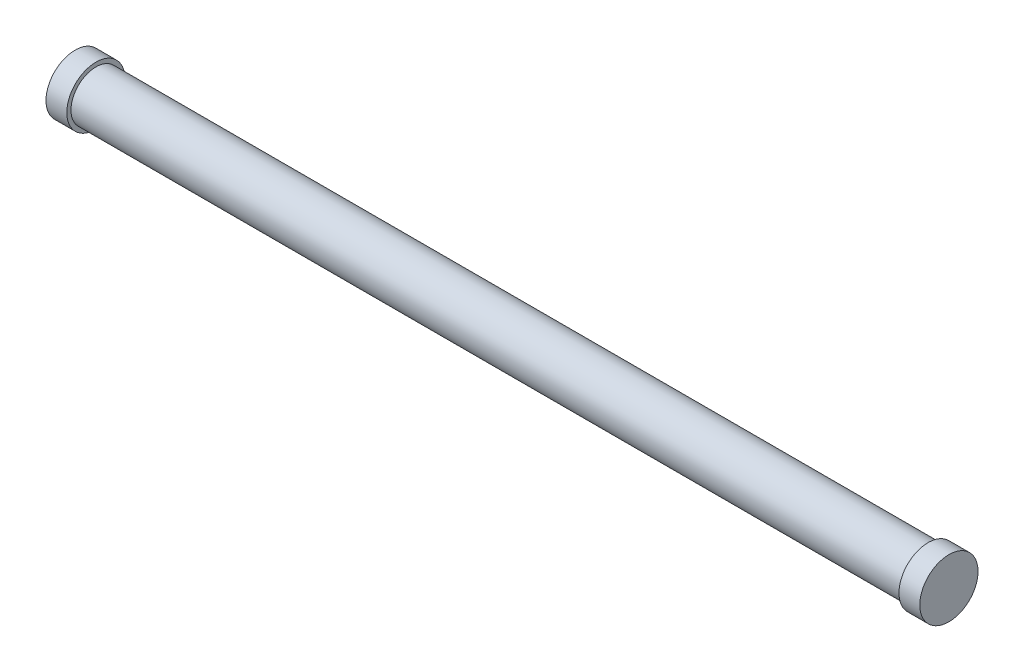
SolidWorks part; units mm, degrees
ref_plane "Front Plane" through (0, 0, 0) normal (0, 0, 1) x (1, 0, 0)
ref_plane "Top Plane" through (0, 0, 0) normal (0, 1, 0) x (1, 0, 0)
ref_plane "Right Plane" through (0, 0, 0) normal (1, 0, 0) x (0, 0, -1)
sketch "Sketch1" plane through (0, 0, 0) normal (0, 1, 0) x (1, 0, 0)
  line L2 (165.2795, 6) -> (165.2795, 12)
  line L3 (165.2795, 12) -> (-34.7205, 12)
  line L4 (-34.7205, 6) -> (-34.7205, 12)
  line L5 (0, 0) -> (-34.7205, 12) construction
  line L6 (165.2795, 12) -> (0, 0) construction
  line L7 (-34.7205, 6) -> (165.2795, 6) construction
  line L8 (-34.7205, 6) -> (165.2795, 6)
  point P0 (0, 0)
  dimension "D1" = 6
  dimension "D2" = 200
revolve "Revolve1" add sketch "Sketch1" angle 360 about L8
sketch "Sketch2" plane through (-34.7205, 0, 0) normal (-1, 0, 0) x (0, 0, 1)
  circle A0 centre (-6, 0) radius 7
extrude "Boss-Extrude1" add sketch "Sketch2" along normal blind 5
ref_plane "Plane1" through (65.2795, 0, 0) normal (1, 0, 0) x (0, 0, -1)
mirror "Mirror1" about plane through (65.2795, 0, 0) normal (1, 0, 0) of "Boss-Extrude1"
